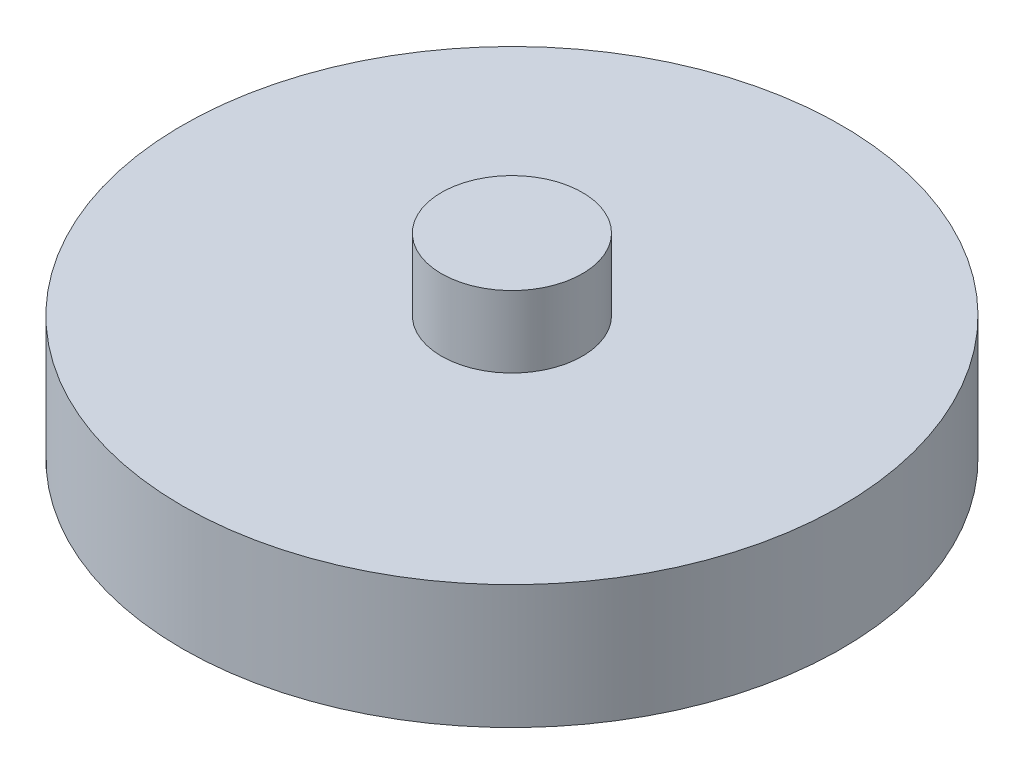
SolidWorks part; units mm, degrees
material "Rubber"
ref_plane "Front Plane" through (0, 0, 0) normal (0, 0, 1) x (1, 0, 0)
ref_plane "Top Plane" through (0, 0, 0) normal (0, 1, 0) x (1, 0, 0)
ref_plane "Right Plane" through (0, 0, 0) normal (1, 0, 0) x (0, 0, -1)
sketch "Sketch1" plane through (0, 0, 0) normal (0, 1, 0) x (1, 0, 0)
  circle A0 centre (0, 0) radius 32.75
  dimension "D1" = 65.5
extrude "Boss-Extrude1" add sketch "Sketch1" along normal blind 12.3
sketch "Sketch2" plane through (0, 12.3, 0) normal (0, 1, 0) x (1, 0, 0)
  line L0 (0, 32.75) -> (0, -32.75) construction
  line L1 (-32.75, 0) -> (32.75, 0) construction
  circle A0 centre (0, 0) radius 32.75 construction
  circle A1 centre (0, 0) radius 7
extrude "Boss-Extrude2" add sketch "Sketch2" along normal blind 7.1
sketch "Sketch4" plane through (0, 0, 0) normal (0, -1, 0) x (1, 0, 0)
  circle A0 centre (0, 0) radius 25
extrude "Cut-Extrude1" cut sketch "Sketch4" against normal blind 3
